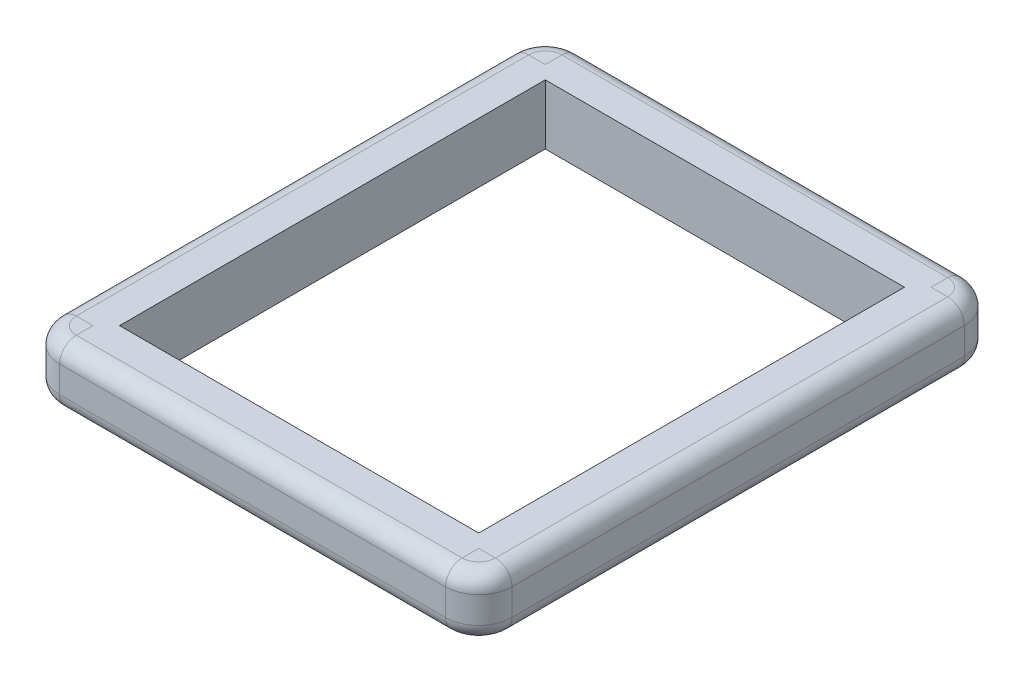
SolidWorks part; units mm, degrees
ref_plane "Front Plane" through (0, 0, 0) normal (0, 0, 1) x (1, 0, 0)
ref_plane "Top Plane" through (0, 0, 0) normal (0, 1, 0) x (1, 0, 0)
ref_plane "Right Plane" through (0, 0, 0) normal (1, 0, 0) x (0, 0, -1)
ref_plane "BumperBottom" through (0, 38.1, 0) normal (0, 1, 0) x (1, 0, 0)
sketch "Sketch2" plane through (0, 0, 0) normal (0, 1, 0) x (1, 0, 0)
  line L0 (368.3, 431.8) -> (368.3, -431.8)
  line L19 (342.9, 406.4) -> (-342.9, 406.4)
  line L20 (342.9, 406.4) -> (342.9, -406.4)
  line L21 (342.9, -406.4) -> (-342.9, -406.4)
  line L22 (-342.9, 406.4) -> (-342.9, -406.4)
  line L23 (342.9, 406.4) -> (-342.9, -406.4) construction
  line L24 (342.9, -406.4) -> (-342.9, 406.4) construction
  line L25 (368.3, -431.8) -> (-368.3, -431.8)
  line L26 (-368.3, 431.8) -> (-368.3, -431.8)
  line L27 (368.3, 431.8) -> (-368.3, 431.8)
  point P0 (0, 0)
  dimension "D1" = 685.8
  dimension "D2" = 812.8
  dimension "D3" = 25.4
extrude "Boss-Extrude1" add sketch "Sketch2" along normal blind 114.3 from surface at 38.1 starting at plane "BumperBottom"
sketch "Sketch3" plane through (0, 0, 431.8) normal (0, 0, 1) x (1, 0, 0)
  line L0 (-368.3, 152.4) -> (-368.3, 38.1) construction
  line L1 (-368.3, 38.1) -> (368.3, 38.1) construction
  line L2 (-368.3, 152.4) -> (368.3, 152.4) construction
  line L3 (-400.05, 152.4) -> (-368.3, 152.4)
  line L4 (-368.3, 152.4) -> (-368.3, 38.1)
  line L5 (-368.3, 38.1) -> (-400.05, 38.1)
  line L6 (-431.8, 120.65) -> (-431.8, 69.85)
  arc A0 (-431.8, 69.85) -> (-400.05, 38.1) centre (-400.05, 69.85) ccw
  arc A1 (-400.05, 152.4) -> (-431.8, 120.65) centre (-400.05, 120.65) ccw
  dimension "D1" = 63.5
sketch "Sketch4" plane through (0, 152.4, 0) normal (0, 1, 0) x (1, 0, 0)
  line L14 (431.8, 495.3) -> (-431.8, 495.3)
  line L15 (-431.8, 495.3) -> (-431.8, -495.3)
  line L16 (-431.8, -495.3) -> (431.8, -495.3)
  line L17 (431.8, -495.3) -> (431.8, 495.3)
  line L18 (368.3, 495.3) -> (-368.3, 495.3)
  line L19 (-431.8, 431.8) -> (-431.8, -431.8)
  line L20 (-368.3, -495.3) -> (368.3, -495.3)
  line L21 (431.8, -431.8) -> (431.8, 431.8)
  arc A0 (368.3, 495.3) -> (431.8, 431.8) centre (368.3, 431.8) cw
  arc A1 (-368.3, 495.3) -> (-431.8, 431.8) centre (-368.3, 431.8) ccw
  arc A2 (-431.8, -431.8) -> (-368.3, -495.3) centre (-368.3, -431.8) ccw
  arc A3 (431.8, -431.8) -> (368.3, -495.3) centre (368.3, -431.8) cw
  dimension "D2" = 63.5
  dimension "D1" = 63.5
sweep "Sweep1" add profiles "Sketch3" path "Sketch4"
